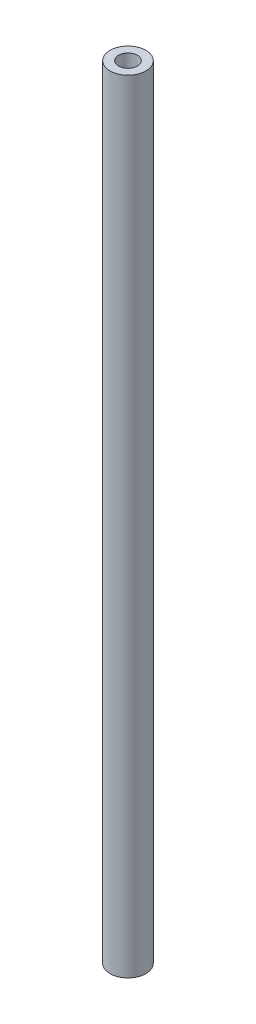
SolidWorks part; units mm, degrees
material "AISI 316 Stainless Steel Sheet (SS)"
ref_plane "Front Plane" through (0, 0, 0) normal (0, 0, 1) x (1, 0, 0)
ref_plane "Top Plane" through (0, 0, 0) normal (0, 1, 0) x (1, 0, 0)
ref_plane "Right Plane" through (0, 0, 0) normal (1, 0, 0) x (0, 0, -1)
sketch "Sketch1" plane through (0, 0, 0) normal (0, 1, 0) x (1, 0, 0)
  circle A0 centre (0, 0) radius 0.3207
  circle A1 centre (0, 0) radius 0.1685
  dimension "D1" = 0.6414
  dimension "D2" = 0.337
extrude "Boss-Extrude1" add sketch "Sketch1" along normal blind 14
